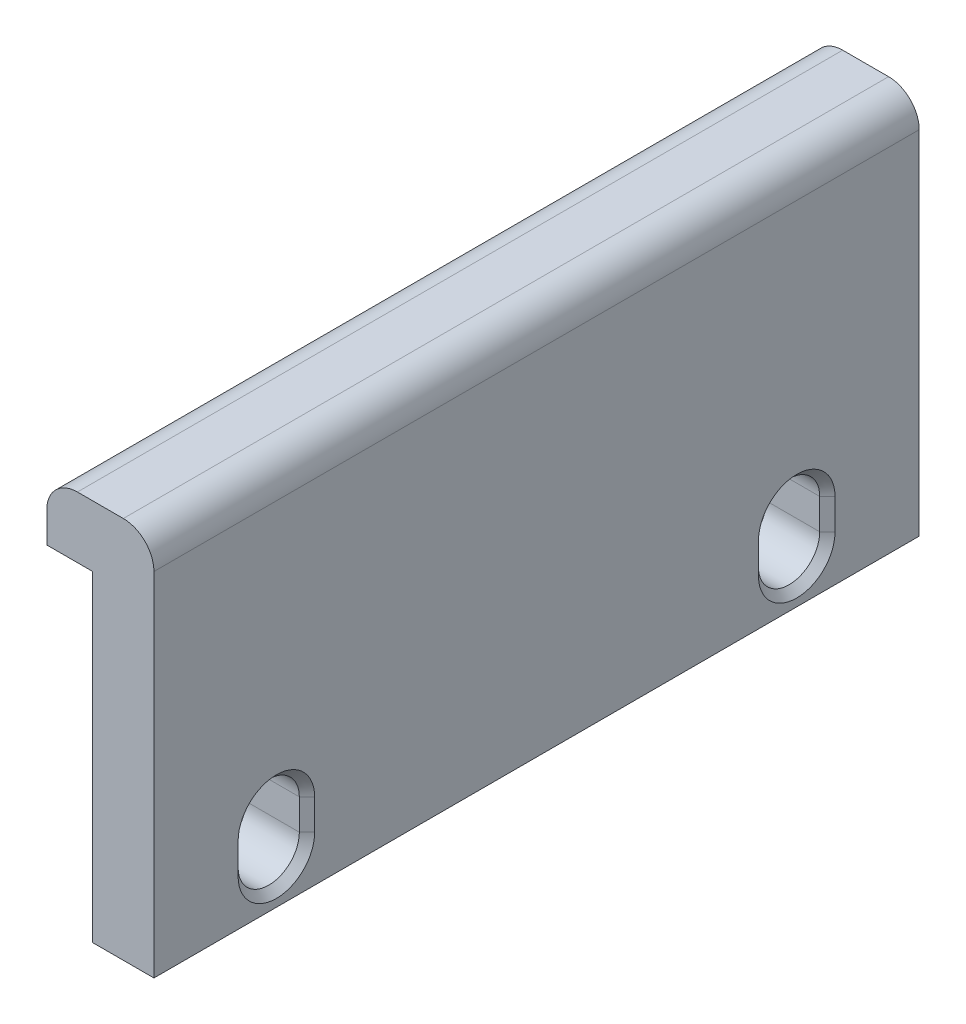
SolidWorks part; units mm, degrees
material "6061-T6 (SS)"
ref_plane "Front Plane" through (0, 0, 0) normal (0, 0, 1) x (1, 0, 0)
ref_plane "Top Plane" through (0, 0, 0) normal (0, 1, 0) x (1, 0, 0)
ref_plane "Right Plane" through (0, 0, 0) normal (1, 0, 0) x (0, 0, -1)
sketch "Sketch1" plane through (0, 0, 0) normal (0, 0, 1) x (1, 0, 0)
  line L1 (4, 25) -> (-3, 25)
  line L2 (-3, 25) -> (-3, 21)
  line L3 (-3, 21) -> (0, 21)
  line L5 (4, 0) -> (4, 25)
  line L6 (0, 0) -> (4, 0)
  line L7 (0, 21) -> (0, 0)
  point P4 (0, 0)
  dimension "D1" = 4
  dimension "D2" = 7
  dimension "D3" = 25
  dimension "D4" = 4
extrude "Boss-Extrude1" add sketch "Sketch1" along normal blind 50
fillet "Fillet1" radius 2 2 edges at (-3, 25, 25) (4, 25, 25)
sketch "Sketch2" plane through (4, 0, 0) normal (1, 0, 0) x (0, 0, -1)
  line L0 (-25, 13.0013) -> (-25, 0) construction
  line L1 (-42, 0) -> (-42, 8) construction
  line L2 (-42, 3) -> (-42, 5) construction
  line L3 (-44, 3) -> (-44, 5)
  line L4 (0, 0) -> (0, 23)
  line L5 (0, 23) -> (-50, 23)
  line L6 (-50, 23) -> (-50, 0)
  line L7 (-50, 0) -> (0, 0)
  line L8 (0, 0) -> (0, 23) construction
  line L9 (0, 23) -> (-50, 23) construction
  line L10 (-50, 23) -> (-50, 0) construction
  line L11 (-50, 0) -> (0, 0) construction
  line L12 (-40, 3) -> (-40, 5)
  line L13 (-8, 3) -> (-8, 5) construction
  line L14 (-6, 3) -> (-6, 5)
  line L15 (-10, 3) -> (-10, 5)
  line L17 (-50, 21) -> (0, 21) construction
  line L18 (-50, 21) -> (0, 21) construction
  arc A0 (-44, 3) -> (-40, 3) centre (-42, 3) ccw
  arc A1 (-40, 5) -> (-44, 5) centre (-42, 5) ccw
  arc A2 (-6, 3) -> (-10, 3) centre (-8, 3) cw
  arc A3 (-10, 5) -> (-6, 5) centre (-8, 5) cw
  point P10 (-42, 4)
  point P17 (-8, 4)
  dimension "D5" = 2
  dimension "D2" = 17
  dimension "D3" = 2
  dimension "D4" = 17
  dimension "D1" = 0
extrude "Cut-Extrude1" cut sketch "Sketch2" against normal up to next contours L12 A1 L3 A0 | A3 L15 A2 L14
chamfer "Chamfer1" distance 0.5 angle 45 8 edges at (4, 7, 8) (4, 4, 6) (4, 4, 10) (4, 1, 8) (4, 7, 42) (4, 4, 44) (4, 4, 40) (4, 1, 42)
